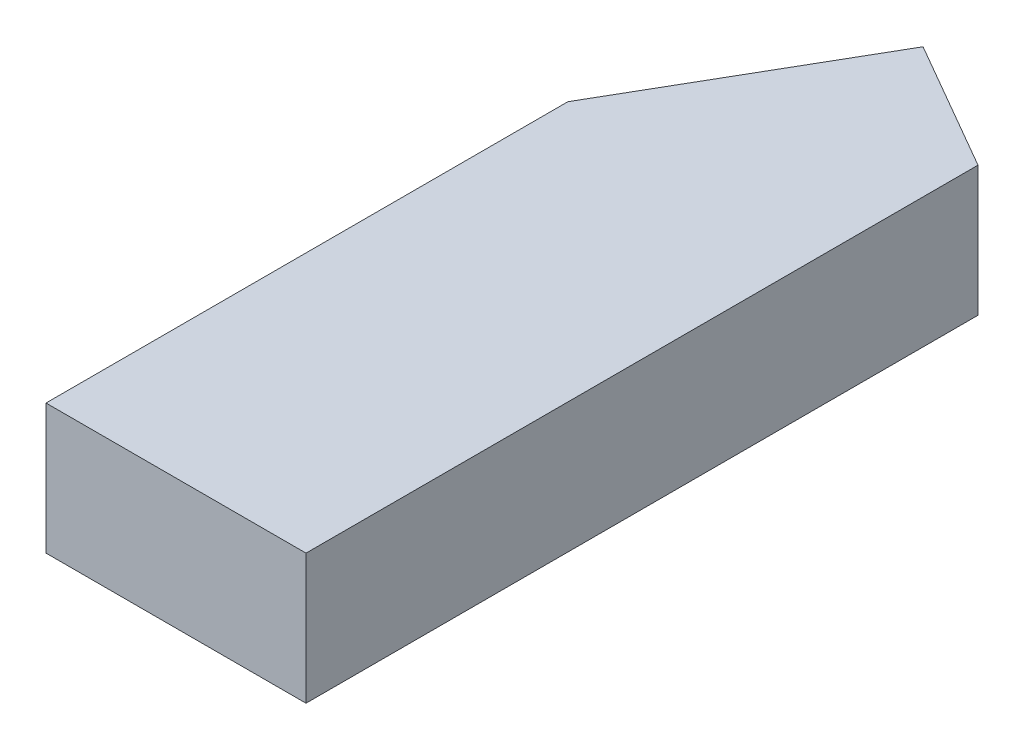
SolidWorks part; units mm, degrees
ref_plane "Front Plane" through (0, 0, 0) normal (0, 0, 1) x (1, 0, 0)
ref_plane "Top Plane" through (0, 0, 0) normal (0, 1, 0) x (1, 0, 0)
ref_plane "Right Plane" through (0, 0, 0) normal (1, 0, 0) x (0, 0, -1)
sketch "Sketch1" plane through (0, 0, 0) normal (0, 1, 0) x (1, 0, 0)
  line L36 (59.9615, -17.0718) -> (39.9615, -17.0718)
  line L40 (39.9615, -17.0718) -> (39.9615, 23.0718)
  line L49 (39.9615, 23.0718) -> (0, 46.1436) construction
  line L50 (59.9615, -17.0718) -> (59.9615, 34.6188)
  line L51 (59.9615, 34.6188) -> (0, 69.2376) construction
  line L52 (39.9615, -23.0718) -> (39.9615, 23.0718) construction
  line L58 (59.9615, 34.6188) -> (49.9615, 40.3923)
  line L63 (39.9615, 23.0718) -> (49.9615, 40.3923)
  line L66 (59.9615, -34.6188) -> (59.9615, 34.6188) construction
  line L68 (0, -46.1436) -> (39.9615, -23.0718) construction
  line L69 (0, -69.2376) -> (59.9615, -34.6188) construction
  line L70 (0, 46.1436) -> (-39.9615, 23.0718) construction
  line L71 (-39.9615, 23.0718) -> (-39.9615, -23.0718) construction
  line L72 (-39.9615, -23.0718) -> (0, -46.1436) construction
  line L76 (-59.9615, 34.6188) -> (-59.9615, -34.6188) construction
  line L77 (-59.9615, -34.6188) -> (0, -69.2376) construction
  line L78 (0, 69.2376) -> (-59.9615, 34.6188) construction
  dimension "D1" = 120
  dimension "D2" = 51.6906
  dimension "D3" = 40.1436
  dimension "D4" = 20
  dimension "D5" = 20
extrude "Boss-Extrude1" add sketch "Sketch1" along normal blind 10
